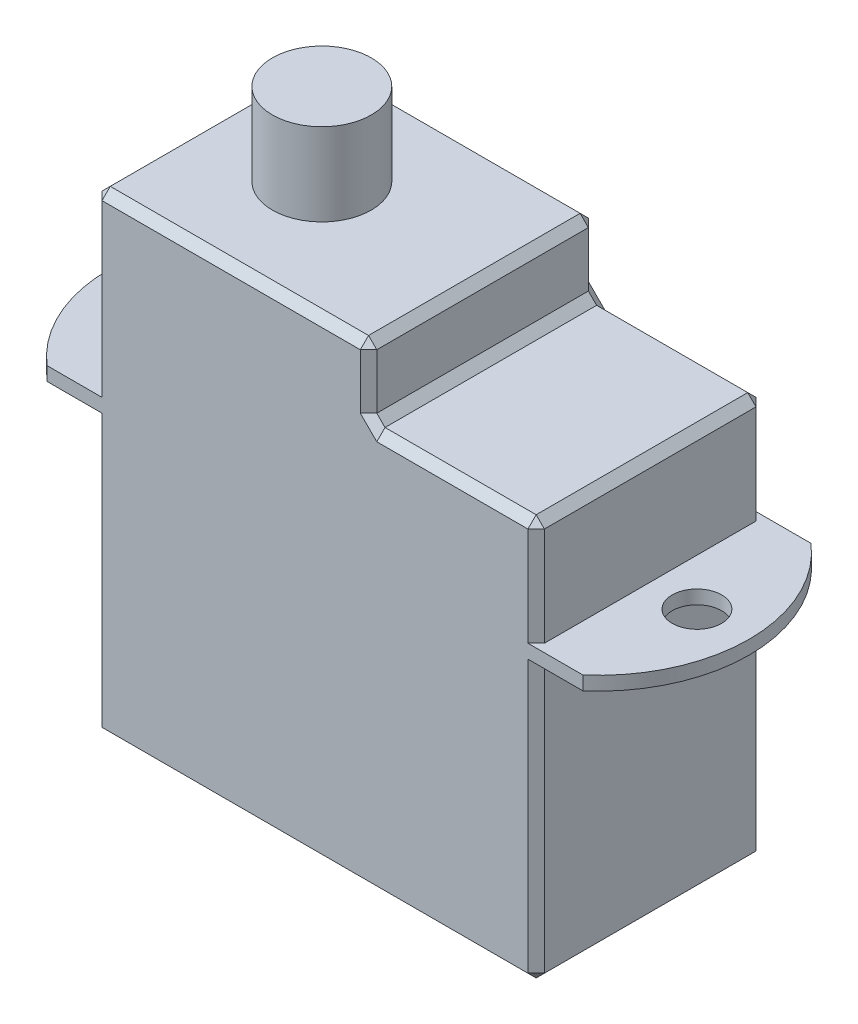
SolidWorks part; units mm, degrees
ref_plane "前视基准面" through (0, 0, 0) normal (0, 0, 1) x (1, 0, 0)
ref_plane "上视基准面" through (0, 0, 0) normal (0, 1, 0) x (1, 0, 0)
ref_plane "右视基准面" through (0, 0, 0) normal (1, 0, 0) x (0, 0, -1)
other "Configuration Table"
sketch "草图1" plane through (0, 0, 0) normal (0, 0, 1) x (1, 0, 0)
  line L28 (16.1, 10.2) -> (17.8, 10.2)
  line L29 (17.8, 10.2) -> (17.8, 10.7)
  line L30 (17.8, 10.7) -> (16.1, 10.7)
  line L31 (16.1, 10.7) -> (16.1, 14.6)
  line L32 (16.1, 14.6) -> (10, 14.6)
  line L33 (10, 14.6) -> (10, 17.2)
  line L34 (10, 17.2) -> (0, 17.2)
  line L35 (0, 17.2) -> (0, 10.7)
  line L36 (0, 10.7) -> (-1.7, 10.7)
  line L37 (-1.7, 10.7) -> (-1.7, 10.2)
  line L38 (-1.7, 10.2) -> (0, 10.2)
  line L39 (0, 10.2) -> (0, 0)
  line L40 (0, 0) -> (16.1, 0)
  line L41 (16.1, 0) -> (16.1, 10.2)
  point P2 (0, 0)
  point P4 (0, 0)
  point P6 (16.1, 10.7)
  dimension "D1" = 0.5
  dimension "D2" = 16.1
  dimension "D3" = 10.2
  dimension "D4" = 17.2
  dimension "D5" = 19.5
  dimension "D6" = 2.6
  dimension "D7" = 10
extrude "凸台-拉伸1" add sketch "草图1" along normal blind 8.3
sketch "草图9" plane through (0, 17.2, 0) normal (0, 1, 0) x (1, 0, 0)
  line L0 (10, 0) -> (0, 0) construction
  line L1 (0, -8.3) -> (0, 0) construction
  circle A0 centre (4, -4) radius 1.8
  dimension "D3" = 3.6
  dimension "D1" = 4
  dimension "D2" = 4
extrude "凸台-拉伸6" add sketch "草图9" along normal blind 3
chamfer "倒角1" distance 0.3 angle 45 22 edges at (0, 0, 4.15) (0, 5.1, 8.3) (8.05, 0, 8.3) (16.1, 5.1, 8.3) (16.1, 0, 4.15) (16.1, 5.1, 0) (8.05, 0, 0) (0, 5.1, 0) (10, 15.9, 8.3) (0, 13.95, 8.3) (16.1, 12.65, 8.3) (13.05, 14.6, 8.3) (5, 17.2, 8.3) (16.1, 14.6, 4.15) (10, 14.6, 4.15) (10, 17.2, 4.15) (0, 17.2, 4.15) (16.1, 12.65, 0) (0, 13.95, 0) (5, 17.2, 0) (10, 15.9, 0) (13.05, 14.6, 0)
sketch "草图10" plane through (0, 10.7, 0) normal (0, 1, 0) x (1, 0, 0)
  line L0 (-1.7, 0) -> (-1.7, -8.3)
  line L1 (17.8, 0) -> (17.8, -8.3)
  line L2 (-3.6, -4.15) -> (-3.6, 14.8999) construction
  line L3 (19.7, -4.15) -> (19.7, 4.8457) construction
  circle A0 centre (1.8822, -4.15) radius 5.4822
  circle A1 centre (14.2178, -4.15) radius 5.4822
  point P14 (11.8028, -4)
  point P15 (9.5412, -4)
  point P16 (6.6005, -4)
  point P17 (3.2837, -4)
  point P20 (-8.9887, -4)
  line M6 (-1.7, 0) -> (-1.7, -8.3)
  dimension "D1" = 23.3
extrude "凸台-拉伸7" add sketch "草图10" against normal up to surface (0.5 mm away) contours A0 M6 | L1 A1
sketch "草图11" plane through (0, 10.7, 0) normal (0, 1, 0) x (1, 0, 0)
  line L0 (-1.7, 0) -> (-1.7, -8.3) construction
  line L1 (17.8, 0) -> (17.8, -8.3) construction
  circle A0 centre (-1.7, -4.15) radius 0.9
  circle A1 centre (17.8, -4.15) radius 0.9
  dimension "D1" = 1.8
  dimension "D2" = 1.8
extrude "切除-拉伸1" cut sketch "草图11" against normal blind 10
